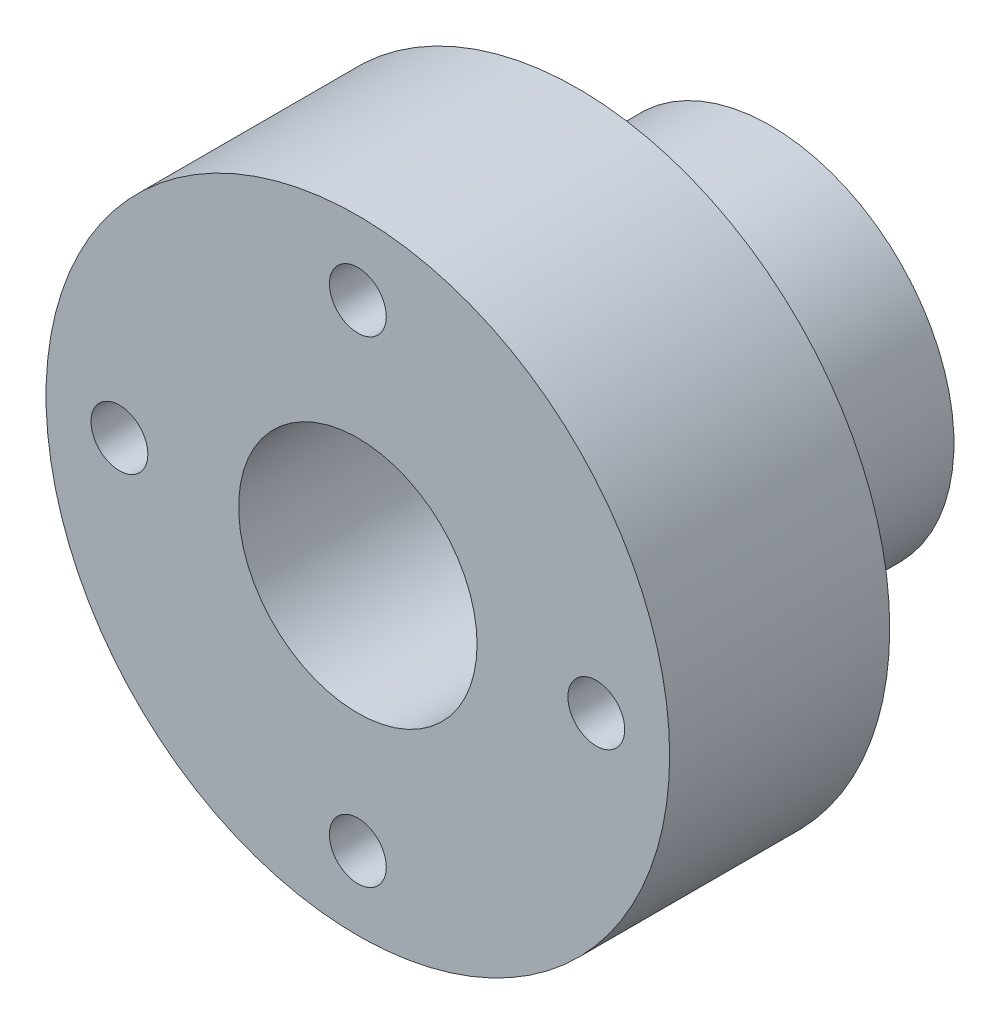
SolidWorks part; units mm, degrees
ref_plane "Front Plane" through (0, 0, 0) normal (0, 0, 1) x (1, 0, 0)
ref_plane "Top Plane" through (0, 0, 0) normal (0, 1, 0) x (1, 0, 0)
ref_plane "Right Plane" through (0, 0, 0) normal (1, 0, 0) x (0, 0, -1)
sketch "Sketch1" plane through (0, 0, 0) normal (0, 0, 1) x (1, 0, 0)
  circle A0 centre (0, 0) radius 10
  dimension "D1" = 20
extrude "Boss-Extrude1" add sketch "Sketch1" along normal blind 10.5
sketch "Sketch3" plane through (0, 0, 10.5) normal (0, 0, 1) x (1, 0, 0)
  circle A0 centre (0, 0) radius 17
  dimension "D1" = 34
extrude "Boss-Extrude2" add sketch "Sketch3" along normal blind 12 contours A0
sketch "Sketch4" plane through (0, 0, 22.5) normal (0, 0, 1) x (1, 0, 0)
  line L0 (0, 0) -> (17.1689, 0) construction
  line L1 (0, -17.3559) -> (0, 16.6078) construction
  circle A0 centre (3, 0) radius 1.55
  circle A1 centre (-3, 0) radius 1.55
  dimension "D1" = 3.1
  dimension "D2" = 3
extrude "Cut-Extrude3" cut sketch "Sketch4" against normal through all
sketch "Sketch5" plane through (0, 0, 22.5) normal (0, 0, 1) x (1, 0, 0)
  line L0 (0, 0) -> (20.7598, 0) construction
  circle A0 centre (0, 0) radius 13 construction
  circle A1 centre (13, 0) radius 1.55
  circle A2 centre (0, -13) radius 1.55
  circle A3 centre (-13, 0) radius 1.55
  circle A4 centre (0, 13) radius 1.55
  point P15 (0, 0)
  dimension "D1" = 26
  dimension "D2" = 3.1
  dimension "D3" = 4
extrude "Cut-Extrude5" cut sketch "Sketch5" against normal through all
sketch "Sketch6" plane through (0, 0, 10.5) normal (0, 0, -1) x (-1, 0, 0)
  circle A0 centre (13, 0) radius 1.75
  circle A1 centre (0, -13) radius 1.75
  circle A2 centre (-13, 0) radius 1.75
  circle A3 centre (0, 13) radius 1.75
  point P12 (0, 0)
  dimension "D1" = 3.5
  dimension "D2" = 4
extrude "Cut-Extrude6" cut sketch "Sketch6" against normal blind 5.2
sketch "Sketch7" plane through (0, 0, 22.5) normal (0, 0, 1) x (1, 0, 0)
  circle A0 centre (3, 0) radius 1.75
  circle A1 centre (-3, 0) radius 1.75
  dimension "D1" = 3.5
  dimension "D2" = 3.5
extrude "Cut-Extrude7" cut sketch "Sketch7" against normal offset from surface (18.5 mm away) 4 up to face at (4.55, 0, 0)
sketch "Sketch8" plane through (0, 0, 22.5) normal (0, 0, 1) x (1, 0, 0)
  circle A0 centre (0, 0) radius 6.5
  dimension "D1" = 13
extrude "Cut-Extrude8" cut sketch "Sketch8" against normal offset from surface (13.5 mm away) 9 up to face at (4.55, 0, 0)
